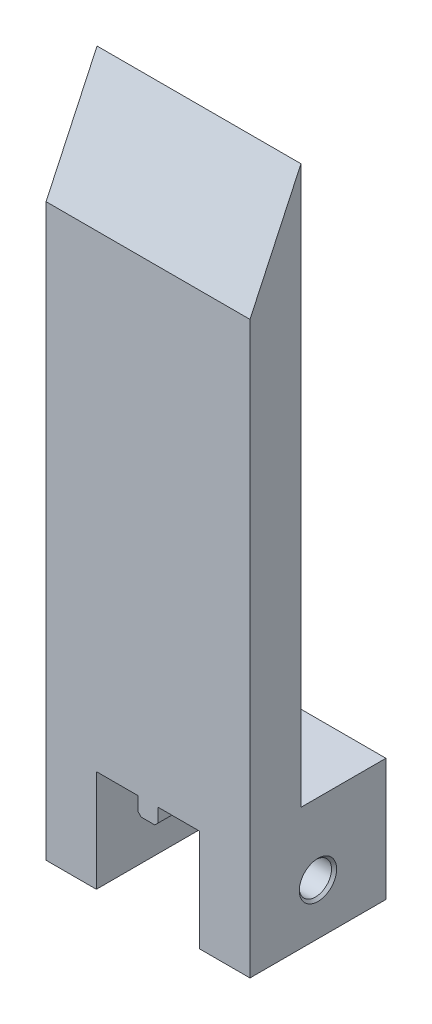
SolidWorks part; units mm, degrees
material "PLA"
ref_plane "정면" through (0, 0, 0) normal (0, 0, 1) x (1, 0, 0)
ref_plane "윗면" through (0, 0, 0) normal (0, 1, 0) x (1, 0, 0)
ref_plane "우측면" through (0, 0, 0) normal (1, 0, 0) x (0, 0, -1)
sketch "스케치1" plane through (0, 0, 0) normal (0, 0, 1) x (1, 0, 0)
  line L1 (-15, 85) -> (15, 85)
  line L2 (-15, 85) -> (-15, -85)
  line L3 (-15, -85) -> (15, -85)
  line L4 (15, 85) -> (15, -85)
  line L5 (-15, 85) -> (15, -85) construction
  line L6 (-15, -85) -> (15, 85) construction
  point P0 (0, 0)
  dimension "D1" = 170
  dimension "D2" = 30
extrude "보스-돌출1" add sketch "스케치1" along normal blind 40
sketch "스케치3" plane through (15, 0, 0) normal (1, 0, 0) x (0, 0, -1)
  line L0 (-40, 85) -> (-40, 52.8324)
  line L2 (-40, 52.8324) -> (-25, 85)
  line L4 (-25, 85) -> (-40, 85)
  dimension "D1" = 25
  dimension "D2" = 15
extrude "컷-돌출1" cut sketch "스케치3" against normal through all
sketch "스케치4" plane through (-15, 0, 0) normal (-1, 0, 0) x (0, 0, 1)
  line L0 (40, -85) -> (0, -85) construction
  line L1 (0, 85) -> (25, 85)
  line L2 (0, 85) -> (0, -79)
  line L3 (0, -79) -> (25, -79)
  line L4 (25, 85) -> (25, -79)
  line L5 (40, 52.8324) -> (25, 85) construction
  dimension "D2" = 6
extrude "컷-돌출2" cut sketch "스케치4" against normal through all
hole_wizard "M5 소켓 머리 캡 나사용 카운터보어2" positions "스케치7" profile "스케치8" counterbore size "M5" standard "KS" end condition through all
sketch "스케치7" plane through (0, -79, 0) normal (0, 1, 0) x (1, 0, 0)
  line L0 (15, 0) -> (-15, 0) construction
  line L1 (15, 0) -> (15, -25) construction
  point P0 (0, -10)
  dimension "D1" = 10
  dimension "D2" = 15
sketch "스케치8" plane through (0, -79, 10) normal (1, 0, 0) x (0, 0, 1)
  line L0 (0, 0) -> (0, 6)
  line L1 (0, 6) -> (2.75, 6)
  line L3 (2.75, 6) -> (2.75, 3)
  line L4 (2.75, 3) -> (5.5, 3)
  line L5 (5.5, 3) -> (5.5, 0)
  line L7 (5.5, 0) -> (0, 0)
  line L11 (0, -6.35) -> (0, 107.95) construction
  dimension "관통 구멍 지름" = 5.5
  dimension "관통 구멍 깊이" = 6
  dimension "카운터보어 지름" = 11
  dimension "카운터보어 깊이" = 3
sketch "스케치9" plane through (0, -85, 0) normal (0, -1, 0) x (1, 0, 0)
  line L0 (-15, 40) -> (15, 40) construction
  line L1 (3, 40) -> (-3, 40)
  line L2 (3, 40) -> (3, 25)
  line L3 (3, 25) -> (-3, 25)
  line L4 (-3, 40) -> (-3, 25)
  line L5 (15, 40) -> (15, 0) construction
  point P6 (0, 40)
  dimension "D1" = 6
  dimension "D2" = 15
  dimension "D3" = 15
extrude "보스-돌출2" add sketch "스케치9" along normal blind 5
chamfer "모따기1" distance 1 angle 45 2 edges at (3, -90, 32.5) (-3, -90, 32.5)
sketch "스케치10" plane through (-15, 0, 0) normal (-1, 0, 0) x (0, 0, 1)
  line L0 (25, -79) -> (0, -79)
  line L1 (0, -79) -> (0, -85)
  line L2 (40, -85) -> (0, -85) construction
  line L3 (0, -85) -> (40, -85)
  line L4 (40, -85) -> (40, 52.8324)
  line L5 (40, 52.8324) -> (25, 85)
  line L6 (40, 52.8324) -> (25, 85) construction
  line L7 (25, -79) -> (25, 85) construction
  line L8 (25, 85) -> (25, -79)
extrude "보스-돌출3" add sketch "스케치10" along normal blind 15
ref_plane "평면1" through (0, 0, 0) normal (-1, 0, 0) x (0, 0, 1)
mirror "대칭 복사1" about plane through (0, 0, 0) normal (-1, 0, 0) of "보스-돌출3"
sketch "스케치11" plane through (0, -85, 0) normal (0, -1, 0) x (1, 0, 0)
  line L0 (-30, 0) -> (30, 0) construction
  line L1 (-30, 40) -> (-15.2, 40)
  line L2 (-30, 40) -> (-30, 0)
  line L3 (-30, 0) -> (-15.2, 0)
  line L4 (-15.2, 40) -> (-15.2, 0)
  line L6 (30, 40) -> (15.2, 40)
  line L7 (30, 40) -> (30, 0)
  line L8 (30, 0) -> (15.2, 0)
  line L9 (15.2, 40) -> (15.2, 0)
  dimension "D1" = 14.8
  dimension "D2" = 14.8
extrude "보스-돌출4" add sketch "스케치11" along normal blind 30
hole_wizard "M5 소켓 머리 캡 나사용 카운터보어1" positions "스케치12" profile "스케치14" counterbore size "M5" standard "KS" end condition up to next
sketch "스케치12" plane through (30, 0, 0) normal (1, 0, 0) x (0, 0, -1)
  line L0 (0, -115) -> (-40, -115) construction
  line L1 (0, -79) -> (0, -115) construction
  point P0 (-20, -100)
  dimension "D1" = 15
  dimension "D2" = 20
sketch "스케치14" plane through (30, -100, 20) normal (0, 1, 0) x (0, 0, -1)
  line L0 (0, 0) -> (0, 14.8)
  line L1 (0, 14.8) -> (2.75, 14.8)
  line L3 (2.75, 14.8) -> (2.75, 12)
  line L4 (4.75, 12) -> (2.75, 12)
  line L5 (4.75, 12) -> (4.75, 0.75)
  line L6 (4.75, 0.75) -> (5.5, 0)
  line L7 (5.5, 0) -> (0, 0)
  line L8 (-4.75, 0.75) -> (-5.5, 0) construction
  line L11 (0, -6.35) -> (0, 107.95) construction
  dimension "관통 구멍 지름" = 5.5
  dimension "관통 구멍 깊이" = 14.8
  dimension "카운터보어 지름" = 9.5
  dimension "카운터보어 깊이" = 12
  dimension "표면 카운터싱크 지름" = 11
  dimension "표면 카운터싱크 각도" = 90
mirror "대칭 복사2" about plane through (0, 0, 0) normal (-1, 0, 0) of "M5 소켓 머리 캡 나사용 카운터보어1"
